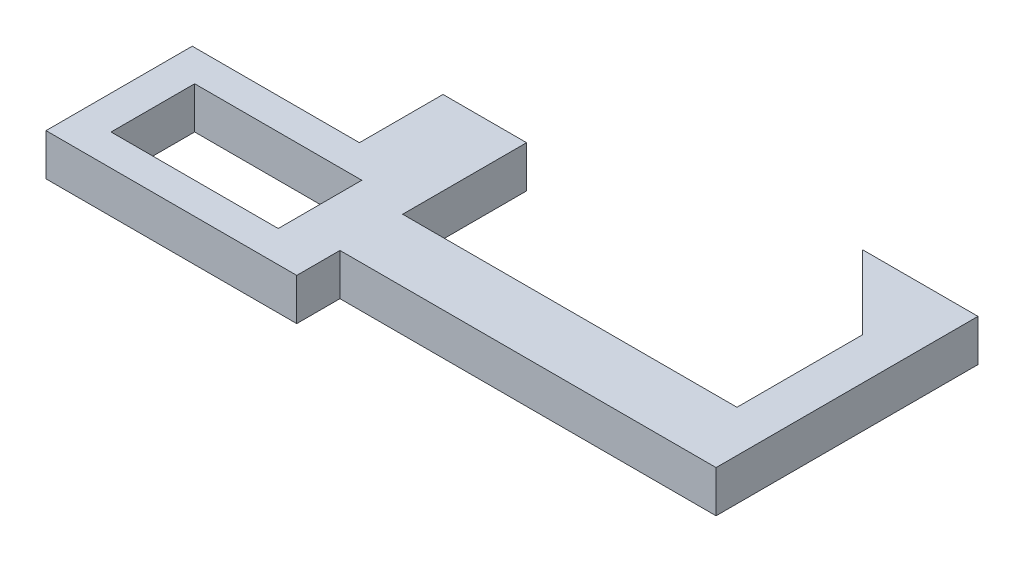
SolidWorks part; units mm, degrees
ref_plane "Front Plane" through (0, 0, 0) normal (0, 0, 1) x (1, 0, 0)
ref_plane "Top Plane" through (0, 0, 0) normal (0, 1, 0) x (1, 0, 0)
ref_plane "Right Plane" through (0, 0, 0) normal (1, 0, 0) x (0, 0, -1)
sketch "Sketch1" plane through (0, 0, 0) normal (0, 1, 0) x (1, 0, 0)
  line L0 (-27.9733, 22.3159) -> (-23.9733, 22.3159)
  line L1 (-23.9733, 22.3159) -> (-23.9733, 23.8159)
  line L2 (-23.9733, 23.8159) -> (-24.8572, 24.6998)
  line L3 (-24.8572, 24.6998) -> (-23.4733, 24.6998)
  line L4 (-23.4733, 24.6998) -> (-23.4733, 21.5659)
  line L5 (-27.9733, 22.3159) -> (-27.9733, 21.5659)
  line L6 (-27.9733, 21.5659) -> (-23.4733, 21.5659)
  line L7 (-27.9733, 22.3159) -> (-27.9733, 22.7989)
  line L8 (-27.9733, 22.7989) -> (-30.9733, 22.7989)
  line L9 (-27.9733, 21.5659) -> (-27.9733, 21.0489)
  line L10 (-27.9733, 21.0489) -> (-30.9733, 21.0489)
  line L11 (-30.9733, 21.0489) -> (-30.9733, 22.7989)
  line L12 (-27.9733, 22.7989) -> (-27.9733, 23.7989)
  line L13 (-27.9733, 23.7989) -> (-28.9732, 23.7989)
  line L14 (-28.9732, 23.7989) -> (-28.9732, 22.7989)
  line L15 (-30.9733, 21.9239) -> (-29.5697, 21.9239)
  line L17 (-30.5697, 22.4239) -> (-28.5697, 22.4239)
  line L18 (-30.5697, 22.4239) -> (-30.5697, 21.4239)
  line L19 (-30.5697, 21.4239) -> (-28.5697, 21.4239)
  line L20 (-28.5697, 22.4239) -> (-28.5697, 21.4239)
  line L21 (-30.5697, 22.4239) -> (-28.5697, 21.4239) construction
  line L22 (-30.5697, 21.4239) -> (-28.5697, 22.4239) construction
extrude "Boss-Extrude1" add sketch "Sketch1" along normal blind 0.5 contours L11 L10 L9 L5 L7 L8 | L5 L6 L4 L3 L2 L1 L0 | L13 L14 L8 L12
